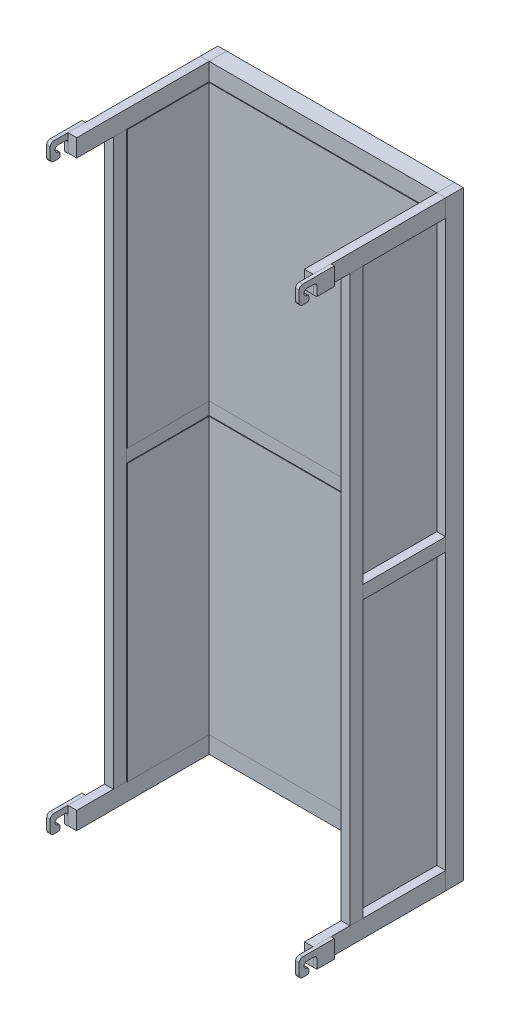
SolidWorks part; units mm, degrees
ref_plane "Front Plane" through (0, 0, 0) normal (0, 0, 1) x (1, 0, 0)
ref_plane "Top Plane" through (0, 0, 0) normal (0, 1, 0) x (1, 0, 0)
ref_plane "Right Plane" through (0, 0, 0) normal (1, 0, 0) x (0, 0, -1)
sketch "Sketch12" plane through (0, 0, 0) normal (0, 1, 0) x (1, 0, 0)
  line L0 (0, 0) -> (-50, 0)
  line L1 (-50, 0) -> (-50, -100)
  line L2 (-50, -100) -> (0, -100)
  line L3 (0, -100) -> (0, 0)
  line L4 (-1340, -100) -> (-1340, 0)
  line L5 (-1390, 0) -> (-1390, -100)
  line L6 (-1390, -100) -> (-1340, -100)
  line L7 (-1340, 0) -> (-1390, 0)
extrude "Boss-Extrude1" add sketch "Sketch12" along normal blind 3400
sketch "Sketch13" plane through (-1340, 0, 0) normal (1, 0, 0) x (0, 0, -1)
  line L0 (0, 3400) -> (0, 0) construction
  line L1 (-100, 0) -> (0, 0)
  line L2 (-100, 0) -> (-100, 100)
  line L3 (-100, 100) -> (0, 100)
  line L4 (0, 0) -> (0, 100)
  line L5 (-100, 3400) -> (-100, 0) construction
  line L6 (-100, 3400) -> (0, 3400)
  line L7 (-100, 3400) -> (-100, 3300)
  line L8 (-100, 3300) -> (0, 3300)
  line L9 (0, 3400) -> (0, 3300)
  line L10 (-100, 0) -> (-100, 1100) construction
  line L11 (-100, 3400) -> (-100, 2300) construction
  line L12 (-100, 1700) -> (-230.0657, 1700) construction
  line L13 (-100, 1100) -> (0, 1100)
  line L14 (-100, 1100) -> (-100, 1300)
  line L15 (-100, 1300) -> (0, 1300)
  line L16 (0, 1100) -> (0, 1300)
  line L17 (-100, 2300) -> (0, 2300)
  line L18 (-100, 2300) -> (-100, 2100)
  line L19 (-100, 2100) -> (0, 2100)
  line L20 (0, 2300) -> (0, 2100)
  line L23 (-100, 1737.5) -> (0, 1737.5)
  line L24 (-100, 1737.5) -> (-100, 1662.5)
  line L25 (-100, 1662.5) -> (0, 1662.5)
  line L26 (0, 1737.5) -> (0, 1662.5)
extrude "Boss-Extrude2" add sketch "Sketch13" along normal up to next separate body
sketch "Sketch14" plane through (0, 0, 100) normal (0, 0, 1) x (1, 0, 0)
  line L1 (-1390, 0) -> (-1340, 0)
  line L2 (-1390, 0) -> (-1390, 100)
  line L3 (-1390, 100) -> (-1340, 100)
  line L4 (-1340, 0) -> (-1340, 100)
  line L5 (0, 0) -> (-50, 0)
  line L6 (0, 0) -> (0, 100)
  line L7 (0, 100) -> (-50, 100)
  line L8 (-50, 0) -> (-50, 100)
  line L9 (-1340, 3300) -> (-1390, 3300)
  line L10 (-1340, 3300) -> (-1340, 3400)
  line L11 (-1340, 3400) -> (-1390, 3400)
  line L12 (-1390, 3300) -> (-1390, 3400)
  line L13 (-50, 3300) -> (0, 3300)
  line L14 (-50, 3300) -> (-50, 3400)
  line L15 (-50, 3400) -> (0, 3400)
  line L16 (0, 3300) -> (0, 3400)
extrude "Boss-Extrude3" add sketch "Sketch14" along normal blind 750 separate body
sketch "Sketch15" plane through (0, 0, 100) normal (0, 0, 1) x (1, 0, 0)
  line L0 (-1390, 1700) -> (-2355.4332, 1700) construction
  line L1 (-1390, 3400) -> (-1390, 0) construction
  line L2 (-1390, 1737.5) -> (-1390, 1662.5)
  line L3 (-1390, 1737.5) -> (-1340, 1737.5)
  line L4 (-1340, 3400) -> (-1340, 0) construction
  line L5 (-1340, 1737.5) -> (-1340, 1662.5)
  line L6 (-1340, 1662.5) -> (-1390, 1662.5)
  line L7 (-50, 1737.5) -> (0, 1737.5)
  line L8 (0, 1662.5) -> (-50, 1662.5)
  line L9 (0, 1737.5) -> (0, 1662.5)
  line L10 (-50, 1737.5) -> (-50, 1662.5)
extrude "Boss-Extrude4" add sketch "Sketch15" along normal blind 467 separate body
sketch "Sketch16" plane through (0, 3300, 0) normal (0, -1, 0) x (1, 0, 0)
  line L0 (0, 100) -> (0, 567) construction
  line L1 (0, 850) -> (0, 100) construction
  line L2 (-50, 850) -> (-50, 100) construction
  line L3 (0, 567) -> (-50, 567)
  line L4 (0, 567) -> (0, 642)
  line L5 (0, 642) -> (-50, 642)
  line L6 (-50, 567) -> (-50, 642)
  line L7 (-1340, 642) -> (-1390, 642)
  line L8 (-1340, 567) -> (-1340, 642)
  line L9 (-1340, 567) -> (-1390, 567)
  line L10 (-1390, 567) -> (-1390, 642)
extrude "Boss-Extrude5" add sketch "Sketch16" along normal up to next (3200 mm away) separate body
sketch "Sketch17" plane through (0, 0, 0) normal (1, 0, 0) x (0, 0, -1)
  line L0 (-850, 0) -> (-850, 54.1)
  line L1 (-895, 10) -> (-895, 24.1)
  line L2 (-930, 0) -> (-905, 0)
  line L3 (-905, 69.1) -> (-865, 69.1)
  line L4 (-750, 101.6) -> (-750, 0)
  line L5 (-750, 0) -> (-850, 0)
  line L6 (-750, 101.6) -> (-930, 101.6)
  line L7 (-950, 20) -> (-950, 81.6)
  line L8 (-905, 3369.1) -> (-865, 3369.1)
  line L9 (-750, 3401.6) -> (-930, 3401.6)
  line L10 (-930, 3300) -> (-905, 3300)
  line L11 (-850, 3300) -> (-850, 3354.1)
  line L12 (-750, 3300) -> (-850, 3300)
  line L13 (-895, 3310) -> (-895, 3324.1)
  line L14 (-750, 3401.6) -> (-750, 3300)
  line L15 (-950, 3320) -> (-950, 3381.6)
  arc A0 (-850, 54.1) -> (-865, 69.1) centre (-865, 54.1) ccw
  arc A1 (-905, 0) -> (-895, 10) centre (-905, 10) ccw
  arc A2 (-950, 20) -> (-930, 0) centre (-930, 20) ccw
  arc A3 (-930, 101.6) -> (-950, 81.6) centre (-930, 81.6) ccw
  arc A4 (-905, 69.1) -> (-905, 34.1) centre (-905, 51.6) ccw
  arc A5 (-895, 24.1) -> (-905, 34.1) centre (-905, 24.1) ccw
  arc A6 (-895, 3324.1) -> (-905, 3334.1) centre (-905, 3324.1) ccw
  arc A7 (-905, 3300) -> (-895, 3310) centre (-905, 3310) ccw
  arc A8 (-905, 3369.1) -> (-905, 3334.1) centre (-905, 3351.6) ccw
  arc A9 (-850, 3354.1) -> (-865, 3369.1) centre (-865, 3354.1) ccw
  arc A10 (-930, 3401.6) -> (-950, 3381.6) centre (-930, 3381.6) ccw
  arc A11 (-950, 3320) -> (-930, 3300) centre (-930, 3320) ccw
extrude "Boss-Extrude6" add sketch "Sketch17" along normal blind 20 separate body
sketch "Sketch18" plane through (-1390, 0, 0) normal (-1, 0, 0) x (0, 0, 1)
  line L0 (950, 3318.4) -> (950, 3380)
  line L1 (750, 3400) -> (750, 3298.4)
  line L2 (895, 3308.4) -> (895, 3322.5)
  line L3 (750, 3298.4) -> (850, 3298.4)
  line L4 (850, 3298.4) -> (850, 3352.5)
  line L5 (930, 3298.4) -> (905, 3298.4)
  line L6 (750, 3400) -> (930, 3400)
  line L7 (905, 3367.5) -> (865, 3367.5)
  line L16 (750, 3349.2) -> (1091.2741, 3349.2) construction
  line L17 (750, 49.2) -> (1105.8983, 49.2) construction
  line L18 (950, 18.4) -> (950, 80)
  line L19 (750, 100) -> (930, 100)
  line L20 (750, -1.6) -> (850, -1.6)
  line L21 (750, 100) -> (750, -1.6)
  line L22 (905, 67.5) -> (865, 67.5)
  line L23 (930, -1.6) -> (905, -1.6)
  line L24 (895, 8.4) -> (895, 22.5)
  line L25 (850, -1.6) -> (850, 52.5)
  arc A0 (950, 3318.4) -> (930, 3298.4) centre (930, 3318.4) cw
  arc A1 (930, 3400) -> (950, 3380) centre (930, 3380) cw
  arc A2 (850, 3352.5) -> (865, 3367.5) centre (865, 3352.5) cw
  arc A3 (905, 3367.5) -> (905, 3332.5) centre (905, 3350) cw
  arc A4 (905, 3298.4) -> (895, 3308.4) centre (905, 3308.4) cw
  arc A5 (895, 3322.5) -> (905, 3332.5) centre (905, 3322.5) cw
  arc A12 (895, 22.5) -> (905, 32.5) centre (905, 22.5) cw
  arc A13 (905, 67.5) -> (905, 32.5) centre (905, 50) cw
  arc A14 (930, 100) -> (950, 80) centre (930, 80) cw
  arc A15 (950, 18.4) -> (930, -1.6) centre (930, 18.4) cw
  arc A16 (905, -1.6) -> (895, 8.4) centre (905, 8.4) cw
  arc A17 (850, 52.5) -> (865, 67.5) centre (865, 52.5) cw
extrude "Boss-Extrude7" add sketch "Sketch18" along normal blind 20 separate body
sketch "Sketch19" plane through (-50, 0, 0) normal (-1, 0, 0) x (0, 0, 1)
  line L1 (567, 3300) -> (100, 3300)
  line L2 (567, 3300) -> (567, 1737.5)
  line L3 (567, 1737.5) -> (100, 1737.5)
  line L4 (100, 3300) -> (100, 1737.5)
  line L5 (567, 1662.5) -> (100, 1662.5)
  line L6 (567, 1662.5) -> (567, 100)
  line L7 (567, 100) -> (100, 100)
  line L8 (100, 1662.5) -> (100, 100)
extrude "Boss-Extrude8" add sketch "Sketch19" along normal blind 4 separate body
sketch "Sketch21" plane through (-1340, 0, 0) normal (1, 0, 0) x (0, 0, -1)
  line L1 (-567, 100) -> (-100, 100)
  line L2 (-567, 100) -> (-567, 1662.5)
  line L3 (-567, 1662.5) -> (-100, 1662.5)
  line L4 (-100, 100) -> (-100, 1662.5)
  line L5 (-567, 1737.5) -> (-100, 1737.5)
  line L6 (-567, 1737.5) -> (-567, 3300)
  line L7 (-567, 3300) -> (-100, 3300)
  line L8 (-100, 1737.5) -> (-100, 3300)
extrude "Boss-Extrude10" add sketch "Sketch21" along normal blind 4 separate body
sketch "Sketch22" plane through (0, 0, 100) normal (0, 0, 1) x (1, 0, 0)
  line L1 (-1336, 100) -> (-54, 100)
  line L2 (-1336, 100) -> (-1336, 1662.5)
  line L3 (-1336, 1662.5) -> (-54, 1662.5)
  line L4 (-54, 100) -> (-54, 1662.5)
  line L5 (-54, 1737.5) -> (-1336, 1737.5)
  line L6 (-54, 1737.5) -> (-54, 3300)
  line L7 (-54, 3300) -> (-1336, 3300)
  line L8 (-1336, 1737.5) -> (-1336, 3300)
extrude "Boss-Extrude11" add sketch "Sketch22" along normal blind 4 separate body
